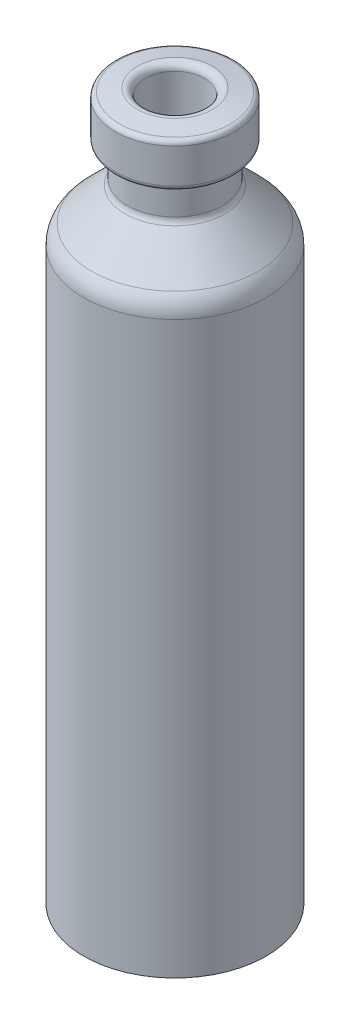
SolidWorks part; units mm, degrees
ref_plane "Front Plane" through (0, 0, 0) normal (0, 0, 1) x (1, 0, 0)
ref_plane "Top Plane" through (0, 0, 0) normal (0, 1, 0) x (1, 0, 0)
ref_plane "Right Plane" through (0, 0, 0) normal (1, 0, 0) x (0, 0, -1)
sketch "Sketch2" plane through (0, 0, 0) normal (1, 0, 0) x (0, 0, -1)
  line L0 (-5.475, 0) -> (-5.475, 17.4824) construction
  dimension "D1" = 5.475
ref_axis "Axis1" through (0, 0, 5.475) along (0, 1, 0)
sketch "Sketch1" plane through (0, 0, 0) normal (1, 0, 0) x (0, 0, -1)
  line L0 (0, 0) -> (0, 34.2328)
  line L1 (-0.85, 0) -> (-0.85, 33.6672)
  line L2 (-0.4741, 35.3695) -> (-2.4769, 37.3533)
  line L3 (-1.3241, 34.8039) -> (-3.5519, 37.0105)
  line L4 (-0.85, 0) -> (0, 0)
  line L5 (-3.7, 37.3658) -> (-3.7, 42.0148)
  line L6 (-3.2237, 42.4074) -> (-2.1428, 42.1973)
  line L7 (-1.9, 41.9028) -> (-1.9, 39.8302)
  line L8 (-2.625, 37.7085) -> (-2.625, 39.1755)
  line L9 (-2.4026, 39.4653) -> (-2.1224, 39.5404)
  line L10 (-5.475, 0) -> (-5.475, 17.4824) construction
  arc A0 (-0.85, 33.6672) -> (-1.3241, 34.8039) centre (-2.45, 33.6672) ccw
  arc A1 (0, 34.2328) -> (-0.4741, 35.3695) centre (-1.6, 34.2328) ccw
  arc A2 (-2.4769, 37.3533) -> (-2.625, 37.7085) centre (-2.125, 37.7085) cw
  arc A3 (-3.5519, 37.0105) -> (-3.7, 37.3658) centre (-3.2, 37.3658) cw
  arc A4 (-2.1428, 42.1973) -> (-1.9, 41.9028) centre (-2.2, 41.9028) cw
  arc A5 (-2.1224, 39.5404) -> (-1.9, 39.8302) centre (-2.2, 39.8302) ccw
  arc A6 (-2.625, 39.1755) -> (-2.4026, 39.4653) centre (-2.325, 39.1755) cw
  arc A7 (-3.7, 42.0148) -> (-3.2237, 42.4074) centre (-3.3, 42.0148) cw
  point P5 (0, 0)
  point P13 (-1.9, 39.6)
  point P14 (-1.9, 39.6)
  point P15 (-1.9, 39.6332)
  point P19 (0, 34.9)
  point P22 (-2.625, 37.5)
  point P25 (-3.7, 37.1573)
  point P30 (-1.9, 39.6)
  point P35 (-3.7, 42.5)
  dimension "D12" = 1.6
  dimension "D13" = 0.5
  dimension "D14" = 0.3
  dimension "D15" = 0.4
  dimension "D1" = 34.9
  dimension "D2" = 0.85
  dimension "D3" = 2.625
  dimension "D4" = 42.5
  dimension "D5" = 79
  dimension "D6" = 5
  dimension "D7" = 1
  dimension "D9" = 1.9
  dimension "D10" = 105
  dimension "D8" = 2.1
  dimension "D11" = 1.775
revolve "Revolve1" add sketch "Sketch1" angle 360 about axis through (0, 0, 5.475) along (0, 1, 0)
equation "\"Height\"= 42.5"
equation "\"D1@Sketch1\"=\"Height\"-7.6"
equation "\"D3@Sketch1\"=10.95/2-5.7/2"
equation "\"D4@Sketch1\"=\"Height\""
equation "\"D5@Sketch1\"=90-11"
equation "\"D9@Sketch1\"=10.95/2-7.15/2"
equation "\"D10@Sketch1\"=90+15"
equation "\"D8@Sketch1\"=5-2.9"
equation "\"D1@Sketch2\"=10.95/2"
equation "\"D11@Sketch1\"=3.55/2"
